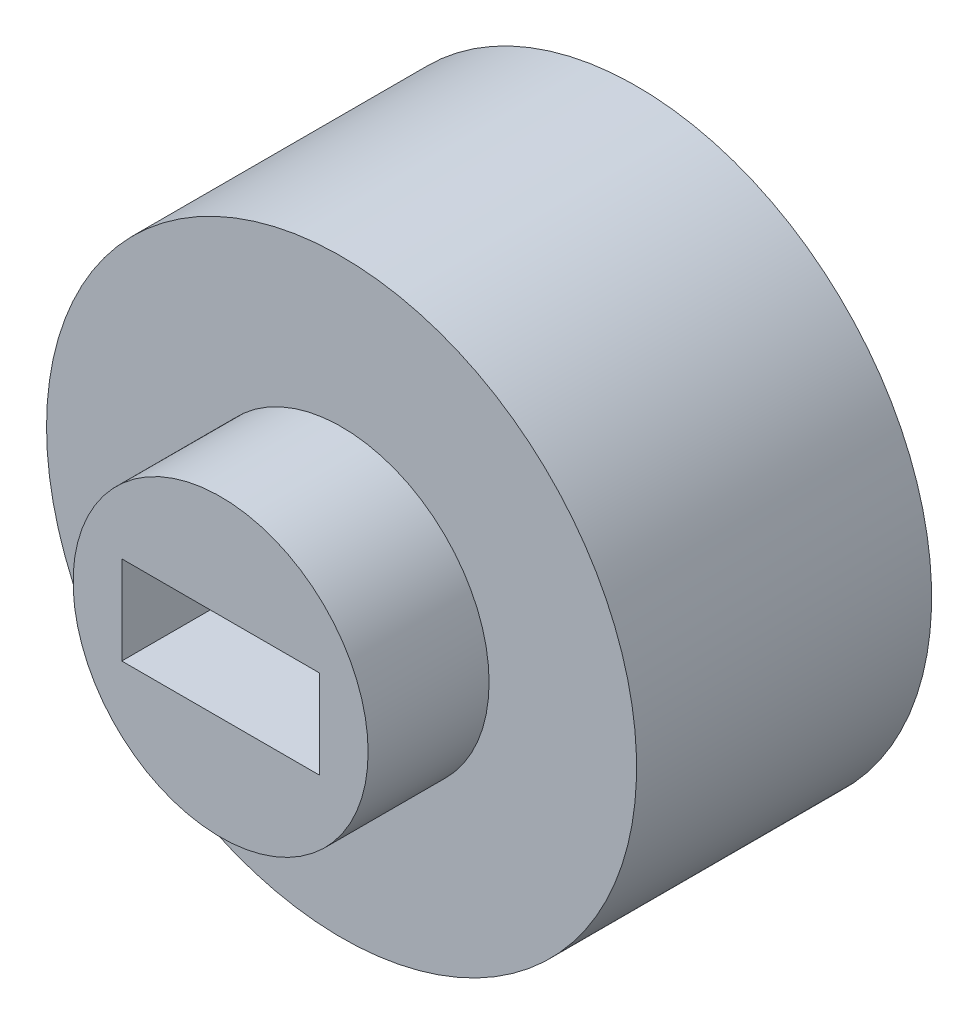
SolidWorks part; units mm, degrees
ref_plane "Front Plane" through (0, 0, 0) normal (0, 0, 1) x (1, 0, 0)
ref_plane "Top Plane" through (0, 0, 0) normal (0, 1, 0) x (1, 0, 0)
ref_plane "Right Plane" through (0, 0, 0) normal (1, 0, 0) x (0, 0, -1)
sketch "Sketch1" plane through (0, 0, 0) normal (0, 0, 1) x (1, 0, 0)
  circle A0 centre (0, 0) radius 50
extrude "Boss-Extrude1" add sketch "Sketch1" along normal blind 41 contours A0
sketch "Sketch2" plane through (0, 0, 41) normal (0, 0, 1) x (1, 0, 0)
  line L1 (-33.5, 15) -> (33.5, 15)
  line L2 (-33.5, 15) -> (-33.5, -15)
  line L3 (-33.5, -15) -> (33.5, -15)
  line L4 (33.5, 15) -> (33.5, -15)
  line L5 (-33.5, 15) -> (33.5, -15) construction
  line L6 (-33.5, -15) -> (33.5, 15) construction
  point P0 (0, 0)
  dimension "D1" = 67
  dimension "D2" = 30
extrude "Cut-Extrude1" cut sketch "Sketch2" against normal blind 41
sketch "Sketch3" plane through (0, 0, 0) normal (0, 0, -1) x (-1, 0, 0)
  circle A0 centre (0, 0) radius 100
extrude "Boss-Extrude2" add sketch "Sketch3" along normal blind 100
